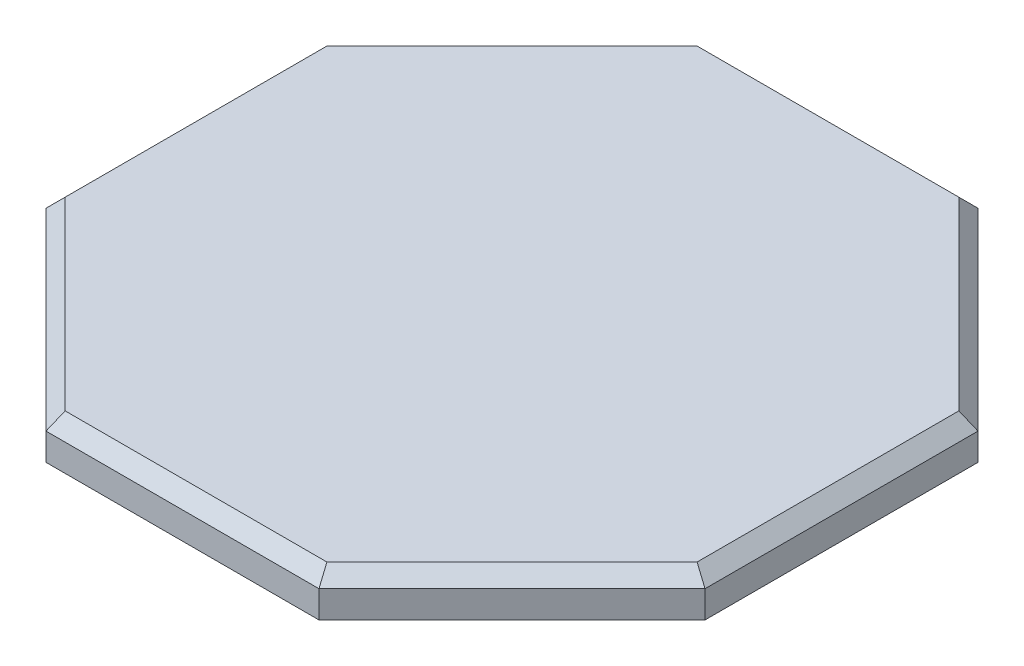
SolidWorks part; units mm, degrees
ref_plane "Plano frontal" through (0, 0, 0) normal (0, 0, 1) x (1, 0, 0)
ref_plane "Plano superior" through (0, 0, 0) normal (0, 1, 0) x (1, 0, 0)
ref_plane "Plano direito" through (0, 0, 0) normal (1, 0, 0) x (0, 0, -1)
sketch "Esboço1" plane through (0, 0, 0) normal (0, 1, 0) x (1, 0, 0)
  line L0 (30.2376, -73) -> (73, -30.2376)
  line L7 (73, 30.2376) -> (30.2376, 73)
  line L8 (30.2376, 73) -> (-30.2376, 73)
  line L9 (-30.2376, 73) -> (-73, 30.2376)
  line L10 (-73, 30.2376) -> (-73, -30.2376)
  line L11 (-73, -30.2376) -> (-30.2376, -73)
  line L12 (-30.2376, -73) -> (30.2376, -73)
  line L13 (73, -30.2376) -> (73, 30.2376)
  circle A0 centre (0, 0) radius 73 construction
  point P12 (73, 0)
  dimension "D1" = 146
extrude "Ressalto-extrusão2" add sketch "Esboço1" along normal blind 9
shell "Casca1" thickness 3
chamfer "Chanfro1" distance 3 angle 45 8 edges at (-51.6188, 9, 51.6188) (-73, 9, 0) (-51.6188, 9, -51.6188) (0, 9, -73) (51.6188, 9, -51.6188) (73, 9, 0) (51.6188, 9, 51.6188) (0, 9, 73)
